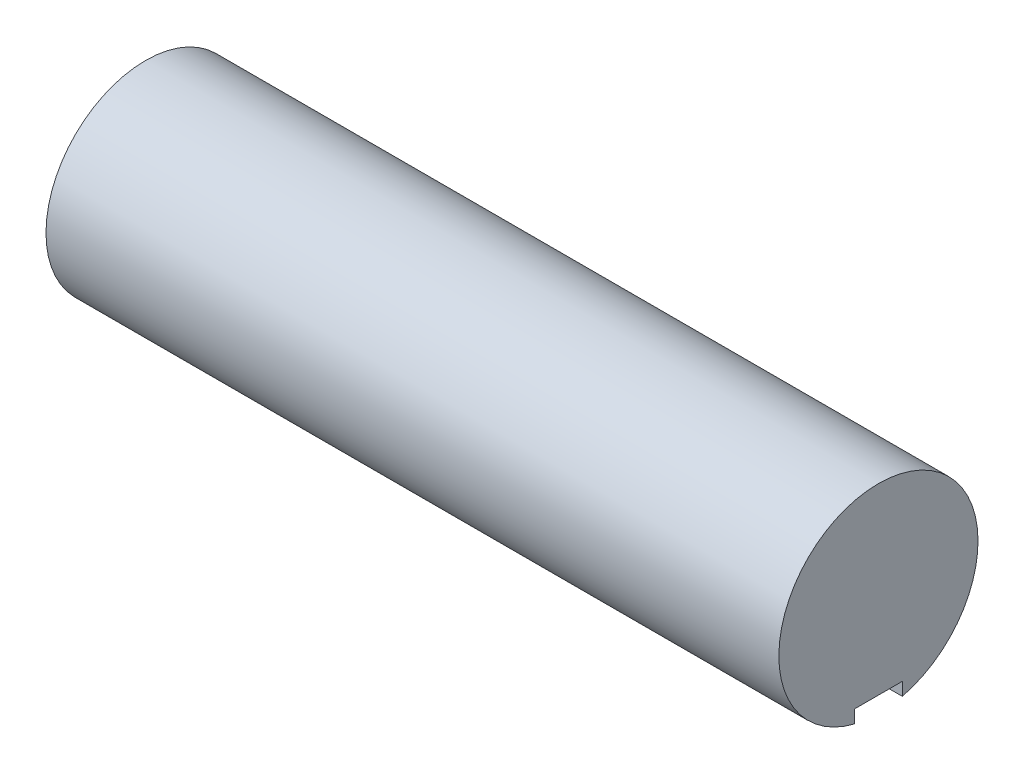
SolidWorks part; units mm, degrees
ref_plane "Front Plane" through (0, 0, 0) normal (0, 0, 1) x (1, 0, 0)
ref_plane "Top Plane" through (0, 0, 0) normal (0, 1, 0) x (1, 0, 0)
ref_plane "Right Plane" through (0, 0, 0) normal (1, 0, 0) x (0, 0, -1)
sketch "Sketch1" plane through (0, 0, 0) normal (1, 0, 0) x (0, 0, -1)
  circle A0 centre (0, 0) radius 6.25
  dimension "D1" = 12.5
extrude "Boss-Extrude1" add sketch "Sketch1" along normal blind 46
sketch "Sketch2" plane through (0, 0, 0) normal (-1, 0, 0) x (0, 0, 1)
  line L1 (-1.5, -7.25) -> (1.5, -7.25)
  line L2 (-1.5, -7.25) -> (-1.5, -5.25)
  line L3 (-1.5, -5.25) -> (1.5, -5.25)
  line L4 (1.5, -7.25) -> (1.5, -5.25)
  line L5 (-1.5, -7.25) -> (1.5, -5.25) construction
  line L6 (-1.5, -5.25) -> (1.5, -7.25) construction
  circle A0 centre (0, 0) radius 6.25 construction
  point P0 (0, -6.25)
  dimension "D1" = 3
  dimension "D2" = 2
extrude "Cut-Extrude1" cut sketch "Sketch2" against normal blind 46
